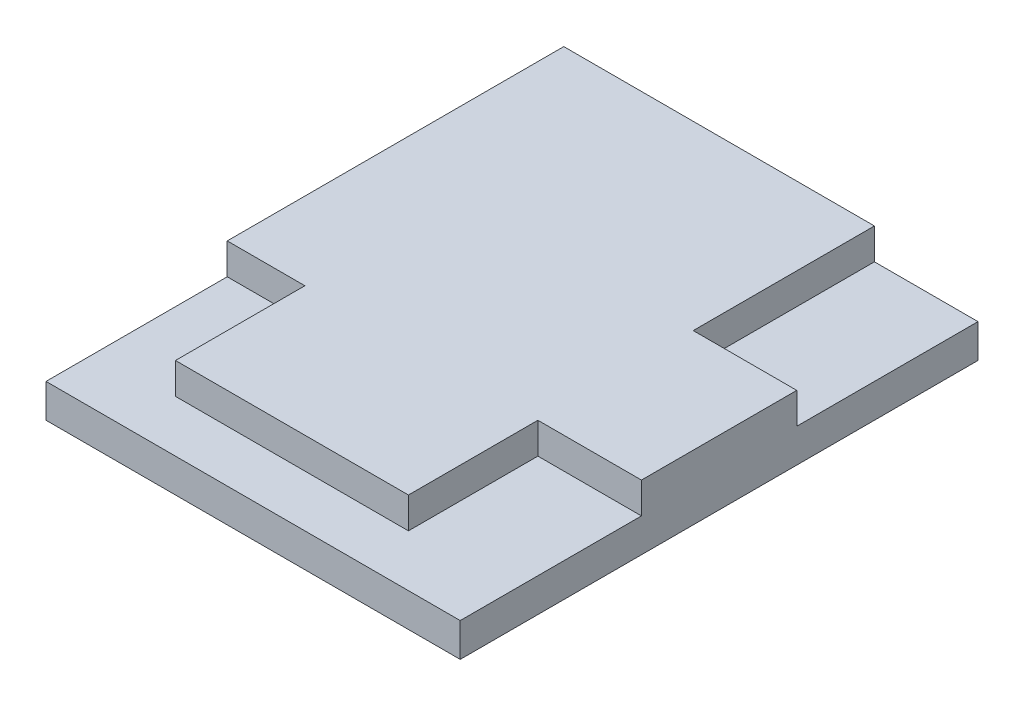
SolidWorks part; units mm, degrees
ref_plane "Front Plane" through (0, 0, 0) normal (0, 0, 1) x (1, 0, 0)
ref_plane "Top Plane" through (0, 0, 0) normal (0, 1, 0) x (1, 0, 0)
ref_plane "Right Plane" through (0, 0, 0) normal (1, 0, 0) x (0, 0, -1)
sketch "Sketch1" plane through (0, 0, 0) normal (0, 1, 0) x (1, 0, 0)
  line L1 (0, 0) -> (16, 0)
  line L2 (0, 0) -> (0, 20)
  line L3 (0, 20) -> (16, 20)
  line L4 (16, 0) -> (16, 20)
  dimension "D1" = 16
  dimension "D2" = 20
extrude "Boss-Extrude1" add sketch "Sketch1" along normal blind 1.3
sketch "Sketch2" plane through (0, 1.3, 0) normal (0, 1, 0) x (1, 0, 0)
  line L15 (0, 0) -> (16, 0) construction
  line L17 (3, 7) -> (3, 2)
  line L18 (3, 2) -> (12, 2)
  line L19 (12, 7) -> (12, 2)
  line L20 (16, 0) -> (16, 20) construction
  line L21 (12, 20) -> (12, 13)
  line L24 (16, 7) -> (12, 7)
  line L30 (0, 20) -> (12, 20)
  line L31 (12, 13) -> (16, 13)
  line L32 (16, 13) -> (16, 7)
  line L33 (0, 20) -> (0, 7)
  line L34 (0, 20) -> (0, 0) construction
  line L35 (0, 7) -> (3, 7)
  dimension "D1" = 2
  dimension "D2" = 4
  dimension "D4" = 7
extrude "Boss-Extrude2" add sketch "Sketch2" along normal blind 1.2
